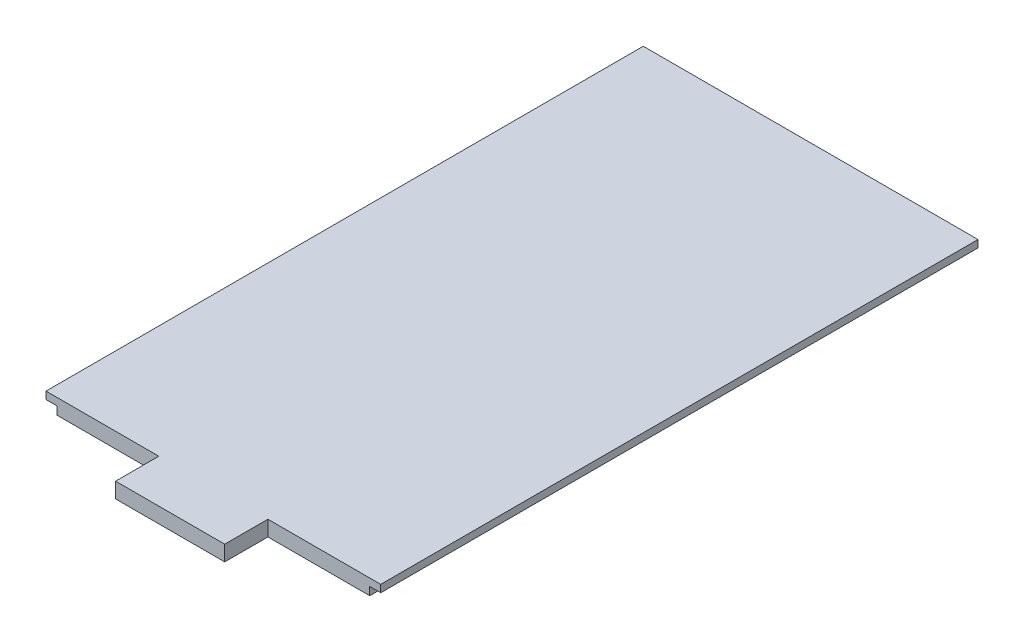
SolidWorks part; units mm, degrees
ref_plane "Front Plane" through (0, 0, 0) normal (0, 0, 1) x (1, 0, 0)
ref_plane "Top Plane" through (0, 0, 0) normal (0, 1, 0) x (1, 0, 0)
ref_plane "Right Plane" through (0, 0, 0) normal (1, 0, 0) x (0, 0, -1)
sketch "Sketch2" plane through (0, 0, 0) normal (0, 0, 1) x (1, 0, 0)
  line L0 (42.7, 0) -> (-42.7, 0)
  line L1 (-42.7, 0) -> (-42.7, 2.2)
  line L2 (-42.7, 2.2) -> (-45.7, 2.2)
  line L3 (-45.7, 2.2) -> (-45.7, 4.2)
  line L4 (-45.7, 4.2) -> (45.7, 4.2)
  line L5 (45.7, 4.2) -> (45.7, 2.2)
  line L6 (45.7, 2.2) -> (42.7, 2.2)
  line L7 (42.7, 2.2) -> (42.7, 0)
  point P0 (0, 4.2)
  point P4 (0, 0)
  dimension "D1" = 2
  dimension "D2" = 91.4
  dimension "D3" = 85.4
  dimension "D4" = 2.2
extrude "Boss-Extrude1" add sketch "Sketch2" along normal blind 163.1
sketch "Sketch3" plane through (0, 0, 0) normal (0, -1, 0) x (1, 0, 0)
  line L0 (-42.7, 163.1) -> (42.7, 163.1) construction
  line L1 (-14.9, 163.1) -> (14.9, 163.1)
  line L2 (-14.9, 163.1) -> (-14.9, 174.9)
  line L3 (-14.9, 174.9) -> (14.9, 174.9)
  line L4 (14.9, 163.1) -> (14.9, 174.9)
  point P6 (0, 163.1)
  dimension "D1" = 11.8
  dimension "D2" = 29.8
extrude "Boss-Extrude2" add sketch "Sketch3" against normal blind 4.2 contours L3 L4 L1 L2
